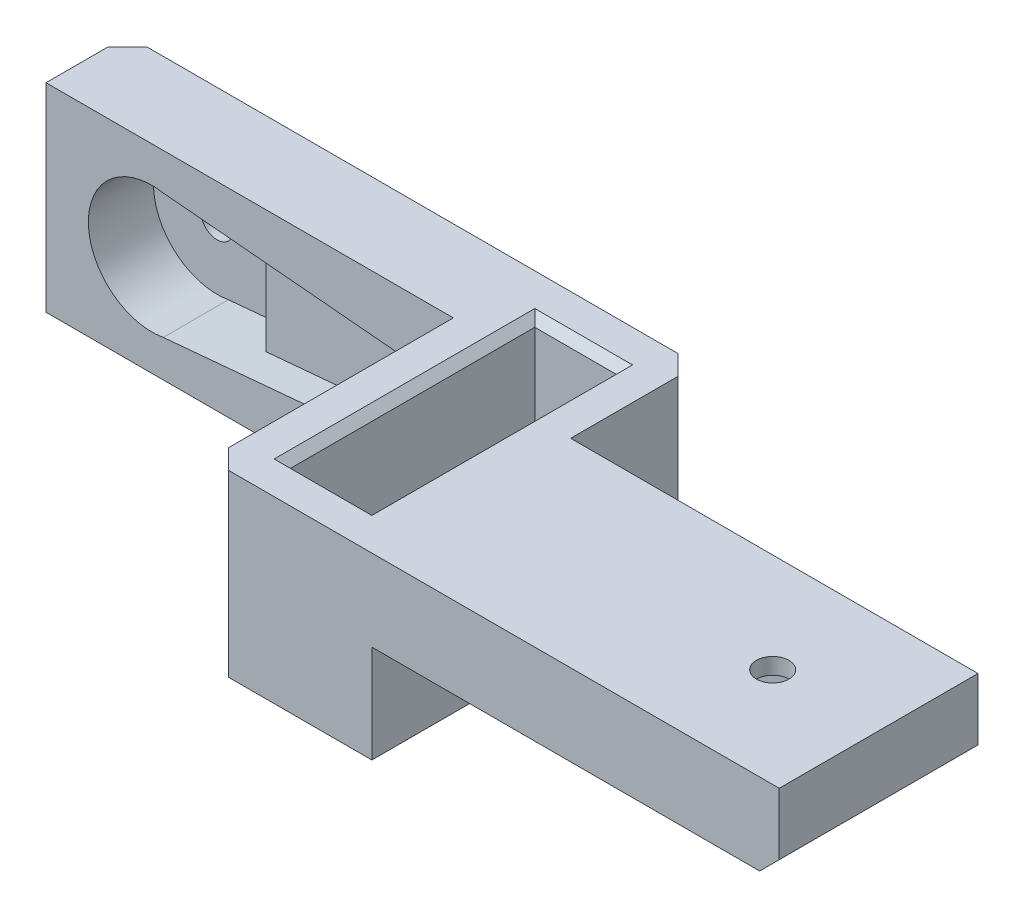
SolidWorks part; units mm, degrees
ref_plane "Front Plane" through (0, 0, 0) normal (0, 0, 1) x (1, 0, 0)
ref_plane "Top Plane" through (0, 0, 0) normal (0, 1, 0) x (1, 0, 0)
ref_plane "Right Plane" through (0, 0, 0) normal (1, 0, 0) x (0, 0, -1)
sketch "Sketch1" plane through (0, 0, 0) normal (0, 0, 1) x (1, 0, 0)
  line L1 (-35.5488, 11.7605) -> (-0.5488, 11.7605)
  line L2 (-35.5488, 11.7605) -> (-35.5488, -0.4395)
  line L3 (-35.5488, -0.4395) -> (-0.5488, -0.4395)
  line L4 (-0.5488, 11.7605) -> (-0.5488, -0.4395)
  dimension "D1" = 35
  dimension "D2" = 12.2
extrude "Boss-Extrude1" add sketch "Sketch1" along normal blind 5
sketch "Sketch2" plane through (0, 0, 5) normal (0, 0, 1) x (1, 0, 0)
  line L0 (-0.5488, 11.7605) -> (-35.5488, 11.7605) construction
  line L3 (-35.5488, 11.7605) -> (-35.5488, -0.4395) construction
  circle A0 centre (-29.0488, 5.6605) radius 1
  dimension "D1" = 2
  dimension "D2" = 6.1
  dimension "D3" = 6.5
extrude "Cut-Extrude1" cut sketch "Sketch2" against normal through all contours A0
sketch "Sketch3" plane through (0, 0, 5) normal (0, 0, 1) x (1, 0, 0)
  line L0 (-35.5488, -0.4395) -> (-0.5488, -0.4395) construction
  line L1 (-0.5488, 11.7605) -> (-10.5488, 11.7605)
  line L2 (-0.5488, 11.7605) -> (-0.5488, -0.4395)
  line L3 (-0.5488, -0.4395) -> (-10.5488, -0.4395)
  line L4 (-10.5488, 11.7605) -> (-10.5488, -0.4395)
  dimension "D1" = 10
extrude "Boss-Extrude2" add sketch "Sketch3" along normal blind 15
sketch "Sketch4" plane through (-0.5488, 0, 0) normal (1, 0, 0) x (0, 0, -1)
  line L1 (-20, 11.7605) -> (-7.8, 11.7605)
  line L2 (-20, 11.7605) -> (-20, 6.7605)
  line L3 (-20, 6.7605) -> (-7.8, 6.7605)
  line L4 (-7.8, 11.7605) -> (-7.8, 6.7605)
  dimension "D1" = 12.2
  dimension "D2" = 5
  dimension "D3" = 12.2
extrude "Boss-Extrude3" add sketch "Sketch4" along normal blind 25 contours L2 L1 L4 L3
sketch "Sketch5" plane through (0, 6.7605, 0) normal (0, -1, 0) x (1, 0, 0)
  line L0 (24.4512, 20) -> (24.4512, 7.8) construction
  line L1 (24.4512, 20) -> (-0.5488, 20) construction
  circle A0 centre (17.9512, 13.9) radius 1
  dimension "D3" = 2
  dimension "D1" = 6.5
  dimension "D2" = 6.1
extrude "Cut-Extrude2" cut sketch "Sketch5" against normal through all and the other way through all contours A0
sketch "Sketch7" plane through (0, 0, 0) normal (0, 0, -1) x (-1, 0, 0)
  line L0 (0.5488, 11.7605) -> (35.5488, 11.7605) construction
  line L1 (23.0488, 5.6605) -> (19.2988, 7.8256)
  line L2 (19.2988, 7.8256) -> (19.2988, 3.4954)
  line L3 (19.2988, 3.4954) -> (23.0488, 5.6605)
  line L5 (35.5488, 11.7605) -> (35.5488, -0.4395) construction
  circle A0 centre (20.5488, 5.6605) radius 1.25 construction
  dimension "D2" = 2.5
  dimension "D1" = 6.1
  dimension "D3" = 15
  dimension "D4" = 3.75
extrude "Cut-Extrude3" cut sketch "Sketch7" against normal blind 0.5
chamfer "Chamfer1" distance 1.2 angle 45 10 edges at (24.4512, 6.7605, 13.9) (-35.5488, 5.6605, 0) (-0.5488, 3.1605, 20) (-0.5488, 5.6605, 0) (-10.5488, -0.4395, 12.5) (-10.5488, 11.7605, 12.5) (-5.5488, -0.4395, 20) (-10.5488, 5.6605, 20) (-18.0488, -0.4395, 0) (-0.5488, -0.4395, 10)
sketch "Sketch8" plane through (0, 0, 5) normal (0, 0, 1) x (1, 0, 0)
  circle A0 centre (-29.0488, 5.6605) radius 3.9
  dimension "D1" = 7.8
extrude "Cut-Extrude4" cut sketch "Sketch8" against normal blind 4
sketch "Sketch10" plane through (0, 0, 5) normal (0, 0, 1) x (1, 0, 0)
  line L0 (-29.0488, 5.6605) -> (-11.0488, 5.6605) construction
  line L1 (-29.0488, 5.6605) -> (-24.0488, 5.6605) construction
  line L2 (-11.0488, 5.6605) -> (-13.5488, 5.6605) construction
  line L3 (-29.0488, 9.5605) -> (-13.5488, 8.1605)
  line L5 (-13.5488, 3.1605) -> (-29.0488, 1.7605)
  line L6 (-29.0488, 1.7605) -> (-29.0488, 9.5605)
  arc A0 (-13.5488, 3.1605) -> (-13.5488, 8.1605) centre (-13.5488, 5.6605) ccw
  circle A1 centre (-29.0488, 5.6605) radius 3.9 construction
  circle A2 centre (-29.0488, 5.6605) radius 3.9 construction
  dimension "D1" = 18
  dimension "D2" = 2.5
  dimension "D3" = 7.8
extrude "Cut-Extrude5" cut sketch "Sketch10" against normal blind 2
sketch "Sketch12" plane through (0, 0, 5) normal (0, 0, 1) x (1, 0, 0)
  line L0 (-24.0488, 5.6605) -> (-24.0488, 9.1089)
  line L1 (-29.0488, 9.5605) -> (-13.5488, 8.1605) construction
  line L2 (-24.0488, 9.1089) -> (-29.0488, 9.5605)
  line L3 (-29.0488, 9.5605) -> (-29.0488, 1.7605)
  line L4 (-29.0488, 1.7605) -> (-24.0488, 2.2121)
  line L5 (-13.5488, 3.1605) -> (-29.0488, 1.7605) construction
  line L6 (-24.0488, 2.2121) -> (-24.0488, 5.6605)
extrude "Cut-Extrude6" cut sketch "Sketch12" against normal blind 4
sketch "Sketch20" plane through (0, 6.7605, 0) normal (0, -1, 0) x (1, 0, 0)
  circle A0 centre (17.9512, 13.9) radius 3.9
  dimension "D1" = 7.8
extrude "Cut-Extrude11" cut sketch "Sketch20" against normal blind 4
sketch "Sketch21" plane through (0, 6.7605, 0) normal (0, -1, 0) x (1, 0, 0)
  line L0 (17.9512, 13.9) -> (-0.287, 13.9) construction
  line L1 (-0.287, 13.9) -> (2.213, 13.9) construction
  line L2 (17.9512, 17.8) -> (2.213, 16.4)
  line L4 (2.213, 11.4) -> (17.9512, 10)
  line L5 (17.9512, 10) -> (17.9512, 17.8)
  arc A0 (2.213, 16.4) -> (2.213, 11.4) centre (2.213, 13.9) ccw
  circle A1 centre (17.9512, 13.9) radius 3.9 construction
  circle A2 centre (17.9512, 13.9) radius 3.9 construction
  dimension "D1" = 18.2383
  dimension "D2" = 2.5
  dimension "D3" = 7.8
extrude "Cut-Extrude12" cut sketch "Sketch21" against normal blind 2
sketch "Sketch22" plane through (0, 6.7605, 0) normal (0, -1, 0) x (1, 0, 0)
  line L0 (17.9512, 13.9) -> (12.9512, 13.9) construction
  line L1 (17.9512, 17.8) -> (17.9512, 10)
  line L2 (17.9512, 10) -> (12.9512, 10.4448)
  line L3 (2.213, 11.4) -> (17.2628, 10.0612) construction
  line L4 (12.9512, 10.4448) -> (12.9512, 17.3552)
  line L5 (17.2628, 17.7388) -> (2.213, 16.4) construction
  line L6 (12.9512, 17.3552) -> (17.9512, 17.8)
  arc A0 (17.2628, 10.0612) -> (17.2628, 17.7388) centre (17.9512, 13.9) ccw construction
  circle A1 centre (17.9512, 13.9) radius 3.9 construction
  dimension "D1" = 5
extrude "Cut-Extrude13" cut sketch "Sketch22" against normal blind 4
sketch "Sketch23" plane through (0, 11.7605, 0) normal (0, 1, 0) x (1, 0, 0)
  line L0 (-1.7488, 0) -> (-34.3488, 0) construction
  line L1 (-8.0488, -2.5) -> (-3.0488, -2.5)
  line L2 (-8.0488, -2.5) -> (-8.0488, -17.5)
  line L3 (-8.0488, -17.5) -> (-3.0488, -17.5)
  line L4 (-3.0488, -2.5) -> (-3.0488, -17.5)
  line L5 (-0.5488, -7.8) -> (-0.5488, -1.2) construction
  line L6 (-10.5488, -18.8) -> (-10.5488, -5) construction
  line L7 (24.4512, -20) -> (-9.3488, -20) construction
  dimension "D1" = 2.5
  dimension "D2" = 2.5
  dimension "D3" = 2.5
  dimension "D4" = 2.5
extrude "Cut-Extrude14" cut sketch "Sketch23" against normal through all
chamfer "Chamfer2" distance 0.5 angle 45 8 edges at (-3.0488, 11.7605, 10) (-5.5488, 11.7605, 2.5) (-5.5488, 11.7605, 17.5) (-8.0488, 11.7605, 10) (-5.5488, -0.4395, 17.5) (-3.0488, -0.4395, 10) (-5.5488, -0.4395, 2.5) (-8.0488, -0.4395, 10)
